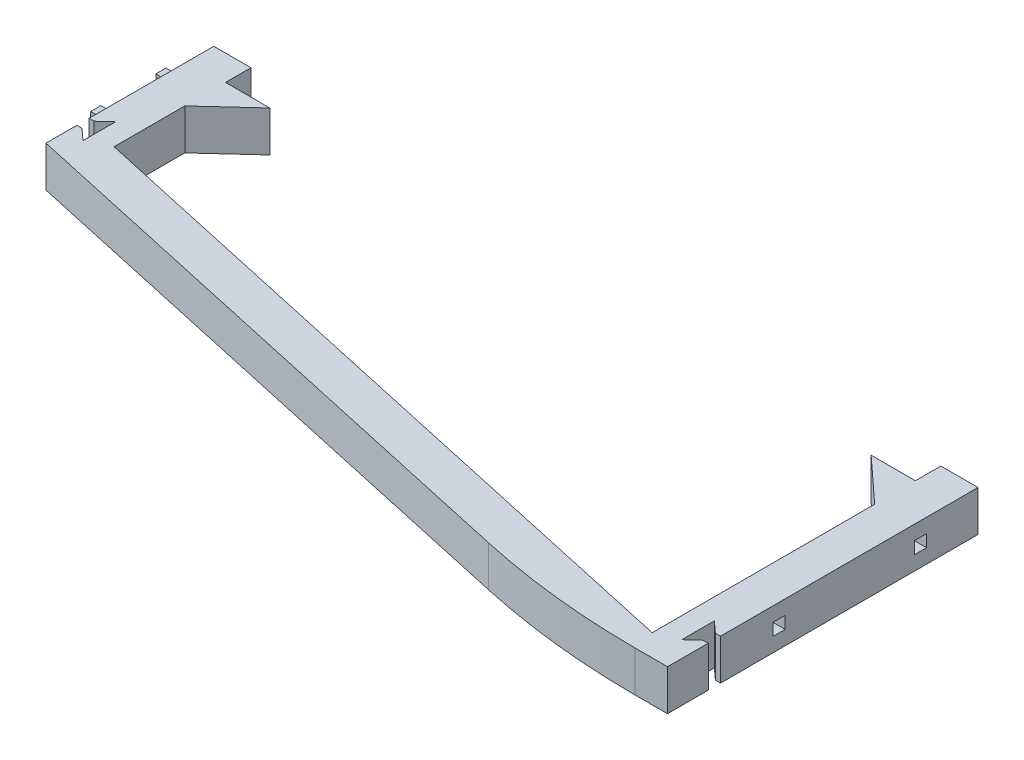
SolidWorks part; units mm, degrees
ref_plane "Přední rovina" through (0, 0, 0) normal (0, 0, 1) x (1, 0, 0)
ref_plane "Horní rovina" through (0, 0, 0) normal (0, 1, 0) x (1, 0, 0)
ref_plane "Pravá rovina" through (0, 0, 0) normal (1, 0, 0) x (0, 0, -1)
sketch "Skica1" plane through (0, 0, 0) normal (0, 1, 0) x (1, 0, 0)
  line L0 (0, 0) -> (0, -66)
  line L1 (0, -66) -> (-150.15, -32.97)
  line L2 (-150.15, -32.97) -> (-150.15, 0)
  line L3 (-150.15, 0) -> (-142.85, 0)
  line L4 (-142.85, 0) -> (-142.85, -26.8965)
  line L5 (-142.85, -26.8965) -> (-7.3, -56.7148)
  line L6 (-7.3, -56.7148) -> (-7.3, 0)
  line L7 (-7.3, 0) -> (0, 0)
  dimension "D1" = 66
  dimension "D2" = 7.3
  dimension "D3" = 7.3
  dimension "D4" = 150.15
  dimension "D5" = 7.5
  dimension "D6" = 32.97
extrude "Přidat vysunutím1" add sketch "Skica1" along normal blind 8
sketch "Skica3" plane through (0, 8, 0) normal (0, 1, 0) x (1, 0, 0)
  line L12 (0, -66) -> (0, 0) construction
  line L13 (-3.2, -48.6) -> (0, -48.6)
  line L14 (-3.2, -48.6) -> (-3.2, -55)
  line L15 (-3.2, -55) -> (0, -55)
  line L16 (0, -48.6) -> (0, -55)
  line L17 (0, -50.6) -> (-1, -50.6)
  line L18 (-1, -50.6) -> (-3.2, -48.6)
  line L19 (-3.2, -55) -> (-1, -53)
  line L20 (-1, -53) -> (0, -53)
  line L21 (0, -53) -> (0, -50.6)
  dimension "D1" = 6.4
  dimension "D2" = 3.2
  dimension "D3" = 2.4
  dimension "D4" = 2
  dimension "D5" = 1
  dimension "D6" = 1
  dimension "D7" = 11
extrude "Odebrat vysunutím1" cut sketch "Skica3" against normal through all contours L19 L20 L16 L17 L18 L14
sketch "Skica6" plane through (0, 8, 0) normal (0, 1, 0) x (1, 0, 0)
  line L0 (-150.15, 0) -> (-150.15, -32.97) construction
  line L9 (-150.15, -5) -> (-134.15, -5)
  line L10 (-150.15, -5) -> (-150.15, -13)
  line L11 (-150.15, -13) -> (-134.15, -13)
  line L12 (-134.15, -5) -> (-134.15, -13)
  line L13 (-142.85, 0) -> (-150.15, 0) construction
  line L14 (0, -50.6) -> (0, 0) construction
  line L15 (0, -5) -> (-16, -5)
  line L16 (0, -5) -> (0, -13)
  line L17 (0, -13) -> (-16, -13)
  line L18 (-16, -5) -> (-16, -13)
  line L19 (0, 0) -> (-7.3, 0) construction
  dimension "D1" = 5
  dimension "D2" = 16
  dimension "D3" = 5
  dimension "D4" = 8
  dimension "D5" = 16
  dimension "D6" = 8
extrude "Přidat vysunutím3" add sketch "Skica6" against normal blind 8 contours L15 L18 L17 L16 | L9 L12 L11 L10
sketch "Skica9" plane through (0, 0, 0) normal (0, -1, 0) x (1, 0, 0)
  line L8 (-142.85, 13) -> (-134.15, 13)
  line L9 (-134.15, 13) -> (-134.15, 5)
  line L10 (-134.15, 5) -> (-142.85, 13)
  line L11 (-16, 13) -> (-7.3, 13)
  line L12 (-7.3, 13) -> (-16, 5)
  line L13 (-16, 5) -> (-16, 13)
extrude "Odebrat vysunutím4" cut sketch "Skica9" against normal through all
sketch "Skica4" plane through (0, 0, 0) normal (1, 0, 0) x (0, 0, -1)
  line L26 (-40.3, 5.2) -> (-37.9, 5.2)
  line L27 (-40.3, 5.2) -> (-40.3, 2.8)
  line L28 (-40.3, 2.8) -> (-37.9, 2.8)
  line L29 (-37.9, 5.2) -> (-37.9, 2.8)
  line L30 (-12.5, 5.2) -> (-10.1, 5.2)
  line L31 (-12.5, 5.2) -> (-12.5, 2.8)
  line L32 (-12.5, 2.8) -> (-10.1, 2.8)
  line L33 (-10.1, 5.2) -> (-10.1, 2.8)
  line L34 (-50.6, 8) -> (0, 8) construction
  line L35 (-66, 0) -> (-53, 0) construction
  line L37 (0, 8) -> (0, 0) construction
  point P18 (-11.3, 2.8)
  dimension "D4" = 10.1
  dimension "D10" = 2.4
  dimension "D11" = 2.4
  dimension "D12" = 2.8
  dimension "D13" = 2.8
  dimension "D14" = 2.4
  dimension "D15" = 2.4
  dimension "D16" = 25.4
extrude "Odebrat vysunutím2" cut sketch "Skica4" against normal blind 4.4
sketch "Skica5" plane through (-150.15, 0, 0) normal (-1, 0, 0) x (0, 0, 1)
  line L0 (0, 8) -> (32.97, 8) construction
  line L1 (5.4, 5) -> (7.4, 5)
  line L2 (5.4, 5) -> (5.4, 3)
  line L3 (5.4, 3) -> (7.4, 3)
  line L4 (7.4, 5) -> (7.4, 3)
  line L5 (18.2, 5) -> (20.2, 5)
  line L6 (18.2, 5) -> (18.2, 3)
  line L7 (18.2, 3) -> (20.2, 3)
  line L8 (20.2, 5) -> (20.2, 3)
  line L9 (0, 8) -> (0, 0) construction
  dimension "D1" = 2
  dimension "D2" = 2
  dimension "D3" = 3
  dimension "D4" = 5.4
  dimension "D5" = 10.8
  dimension "D6" = 2
  dimension "D7" = 2
  dimension "D8" = 3
extrude "Přidat vysunutím2" add sketch "Skica5" along normal blind 4
sketch "Skica10" plane through (0, 8, 0) normal (0, 1, 0) x (1, 0, 0)
  line L0 (-150.15, -26.9) -> (-149.15, -26.9)
  line L5 (-142.85, 0) -> (-150.15, 0) construction
  line L6 (-150.15, 0) -> (-150.15, -32.97) construction
  line L7 (-150.15, -24.5) -> (-149.15, -24.5)
  line L8 (-149.15, -24.5) -> (-146.95, -22.5)
  line L9 (-146.95, -22.5) -> (-146.95, -28.9)
  line L10 (-146.95, -28.9) -> (-149.15, -26.9)
  line L11 (-150.15, -26.9) -> (-150.15, -24.5)
  dimension "D1" = 6.4
  dimension "D2" = 2.4
  dimension "D3" = 1
  dimension "D4" = 1
  dimension "D5" = 2
  dimension "D6" = 3.2
  dimension "D7" = 22.5
extrude "Odebrat vysunutím5" cut sketch "Skica10" against normal through all
sketch "Skica11" plane through (0, 8, 0) normal (0, 1, 0) x (1, 0, 0)
  line L0 (0, -61) -> (-22.7293, -61)
  line L1 (0, -66) -> (0, -53) construction
  line L2 (-150.15, -32.97) -> (0, -66) construction
  line L3 (-22.7293, -61) -> (0, -66)
  line L4 (0, -66) -> (0, -61)
  dimension "D1" = 5
extrude "Odebrat vysunutím6" cut sketch "Skica11" against normal through all
fillet "Zaoblit1" radius 150 1 edges at (-22.7293, 4, 61)
